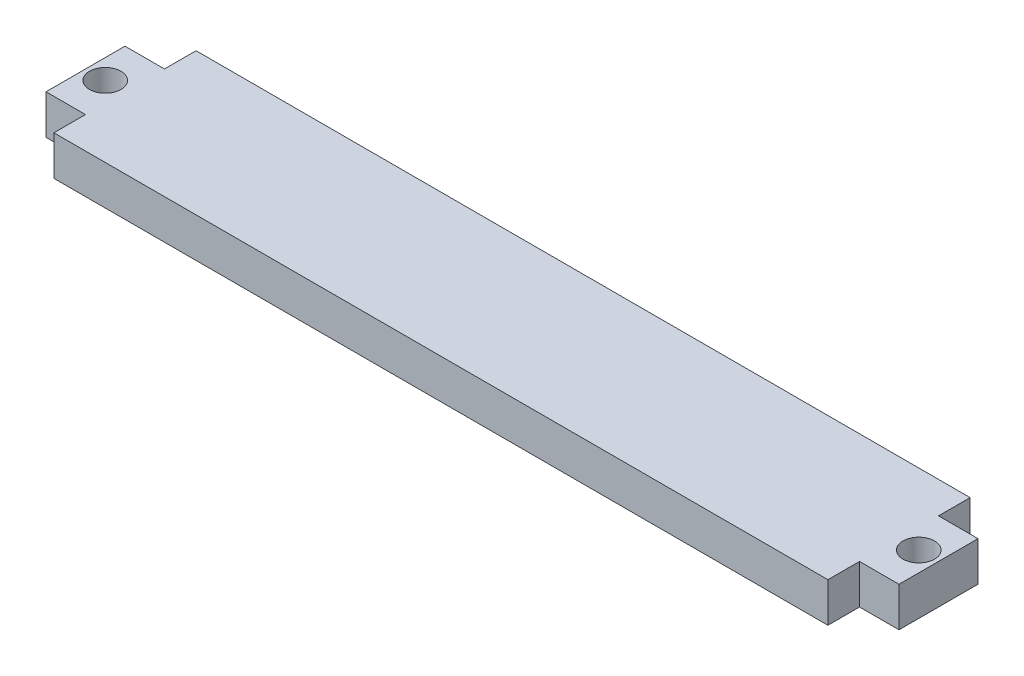
SolidWorks part; units mm, degrees
ref_plane "Front Plane" through (0, 0, 0) normal (0, 0, 1) x (1, 0, 0)
ref_plane "Top Plane" through (0, 0, 0) normal (0, 1, 0) x (1, 0, 0)
ref_plane "Right Plane" through (0, 0, 0) normal (1, 0, 0) x (0, 0, -1)
sketch "Sketch1" plane through (0, 0, 0) normal (0, 1, 0) x (1, 0, 0)
  line L0 (0.1262, -0.9677) -> (0.1262, 17.0323) construction
  line L1 (-48.8738, 17.0323) -> (49.1262, 17.0323)
  line L2 (-53.8738, 13.0323) -> (-53.8738, 3.0323)
  line L3 (-48.8738, -0.9677) -> (49.1262, -0.9677)
  line L4 (54.1262, 13.0323) -> (54.1262, 3.0323)
  line L5 (-41.8738, 8.0323) -> (54.1262, 8.0323) construction
  line L6 (49.1262, 17.0323) -> (49.1262, 13.0323)
  line L9 (-53.8738, 13.0323) -> (-48.8738, 13.0323)
  line L10 (-48.8738, 17.0323) -> (-48.8738, 13.0323)
  line L11 (54.1262, 13.0323) -> (49.1262, 13.0323)
  line L12 (54.1262, 3.0323) -> (49.1262, 3.0323)
  line L13 (49.1262, -0.9677) -> (49.1262, 3.0323)
  line L14 (-48.8738, -0.9677) -> (-48.8738, 3.0323)
  line L15 (-53.8738, 3.0323) -> (-48.8738, 3.0323)
  line L16 (-4.8738, 13.5323) -> (5.1244, 13.5323)
  line L17 (0.1262, 13.5323) -> (0.1262, 2.9843) construction
  line L18 (2.1262, 9.5323) -> (2.1262, 2.5323)
  line L19 (-4.8738, 9.5323) -> (-1.8738, 9.5323)
  line L20 (5.1262, 9.5323) -> (2.1262, 9.5323)
  line L21 (-14.8738, 1.0323) -> (-14.8738, 9.8783)
  line L22 (-14.8738, 9.8783) -> (-9.8056, 14.9465)
  line L23 (15.1262, 1.0323) -> (15.1262, 9.8783)
  line L24 (3.1262, 8.5323) -> (6.1262, 8.5323)
  line L25 (-5.8271, 14.5323) -> (6.0795, 14.5323)
  line L26 (-2.8738, 8.5323) -> (-5.8738, 8.5323)
  line L27 (-2.8738, 8.5323) -> (-2.8738, 1.5323)
  line L28 (3.1262, 8.5323) -> (3.1262, 1.5323)
  line L29 (15.1262, 9.8783) -> (10.058, 14.9465)
  line L30 (-13.8738, 2.0323) -> (-13.8738, 9.464)
  line L31 (-13.8738, 9.464) -> (-9.8056, 13.5323)
  line L32 (-9.8056, 14.9465) -> (-9.8056, 11.6498) construction
  line L33 (14.1262, 2.0323) -> (14.1262, 9.464)
  line L34 (14.1262, 9.464) -> (10.058, 13.5323)
  line L35 (-1.8738, 9.5323) -> (-1.8738, 2.5323)
  line L36 (51.6262, 13.0323) -> (51.6262, 3.0323) construction
  circle A0 centre (51.6262, 8.0323) radius 2
  circle A1 centre (-51.3738, 8.0323) radius 2
  dimension "D21" = 4
  dimension "D1" = 108
  dimension "D2" = 18
  dimension "D3" = 4
  dimension "D4" = 5
  dimension "D5" = 5
  dimension "D6" = 9.9982
  dimension "D7" = 3
  dimension "D8" = 15
  dimension "D9" = 1
  dimension "D10" = 3
  dimension "D11" = 7
  dimension "D12" = 1
  dimension "D13" = 1
  dimension "D14" = 1
  dimension "D15" = 135
  dimension "D16" = 4
  dimension "D17" = 4
  dimension "D18" = 2.5
  dimension "D19" = 3
  dimension "D20" = 2
  dimension "D22" = 7
  dimension "D23" = 4
  dimension "D24" = 4
  dimension "D25" = 1
extrude "Boss-Extrude1" add sketch "Sketch1" along normal blind 5
